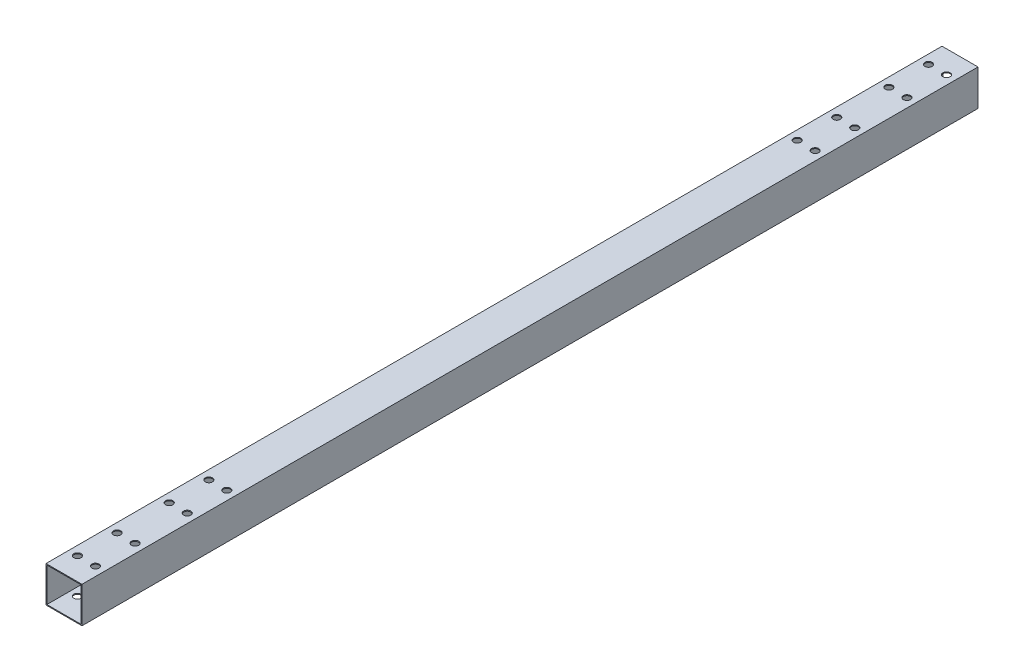
SolidWorks part; units mm, degrees
ref_plane "前视基准面" through (0, 0, 0) normal (0, 0, 1) x (1, 0, 0)
ref_plane "上视基准面" through (0, 0, 0) normal (0, 1, 0) x (1, 0, 0)
ref_plane "右视基准面" through (0, 0, 0) normal (1, 0, 0) x (0, 0, -1)
sketch "草图1" plane through (0, 0, 0) normal (0, 0, 1) x (1, 0, 0)
  line L1 (-9.5, -9.5) -> (9.5, -9.5)
  line L2 (-9.5, -9.5) -> (-9.5, 9.5)
  line L3 (-9.5, 9.5) -> (9.5, 9.5)
  line L4 (9.5, -9.5) -> (9.5, 9.5)
  line L5 (-9.5, -9.5) -> (9.5, 9.5) construction
  line L6 (-9.5, 9.5) -> (9.5, -9.5) construction
  line L7 (-10, -10) -> (10, -10)
  line L8 (-10, -10) -> (-10, 10)
  line L9 (-10, 10) -> (10, 10)
  line L10 (10, -10) -> (10, 10)
  line L11 (-10, -10) -> (10, 10) construction
  line L12 (-10, 10) -> (10, -10) construction
  point P0 (0, 0)
  point P6 (0, 0)
  dimension "D1" = 20
  dimension "D2" = 20
  dimension "D3" = 19
  dimension "D4" = 19
extrude "凸台-拉伸1" add sketch "草图1" along normal blind 498
sketch "草图2" plane through (0, 10, 0) normal (0, 1, 0) x (1, 0, 0)
  line L0 (10, 0) -> (-10, 0) construction
  line L1 (-5, -1012.5) -> (-5, 48987.5) construction
  line L2 (0, -1000) -> (0, 49000) construction
  line L3 (10, -498) -> (-10, -498) construction
  circle A0 centre (-5, -12.5) radius 2
  circle A1 centre (-5, -34.5) radius 2
  circle A2 centre (-5, -85.5) radius 2
  circle A3 centre (-5, -63.5) radius 2
  circle A4 centre (-5, -434.5) radius 2
  circle A5 centre (-5, -412.5) radius 2
  circle A6 centre (-5, -463.5) radius 2
  circle A7 centre (-5, -485.5) radius 2
  circle A8 centre (5, -485.5) radius 2
  circle A9 centre (5, -463.5) radius 2
  circle A10 centre (5, -434.5) radius 2
  circle A11 centre (5, -412.5) radius 2
  circle A12 centre (5, -85.5) radius 2
  circle A13 centre (5, -63.5) radius 2
  circle A14 centre (5, -34.5) radius 2
  circle A15 centre (5, -12.5) radius 2
  point P20 (-5, -418.439)
  dimension "D1" = 4
  dimension "D2" = 12.5
  dimension "D3" = 22
  dimension "D6" = 29
  dimension "D7" = 12.5
  dimension "D8" = 22
  dimension "D9" = 29
  dimension "D10" = 22
  dimension "D4" = 22
  dimension "D5" = 5
extrude "切除-拉伸1" cut sketch "草图2" against normal blind 20
